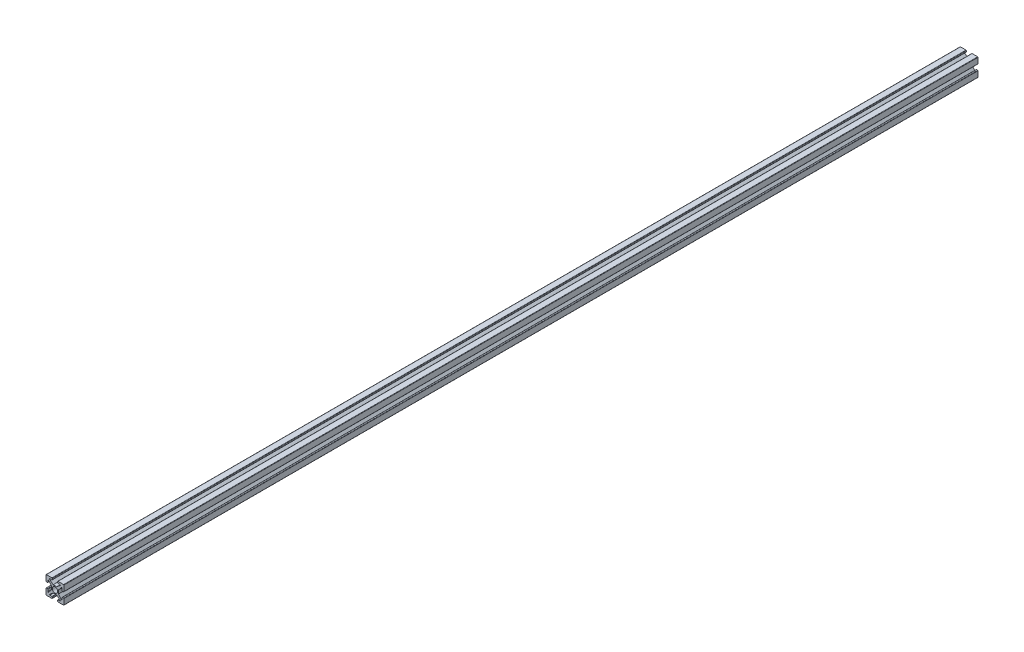
SolidWorks part; units mm, degrees
ref_plane "Front Plane" through (0, 0, 0) normal (0, 0, 1) x (1, 0, 0)
ref_plane "Top Plane" through (0, 0, 0) normal (0, 1, 0) x (1, 0, 0)
ref_plane "Right Plane" through (0, 0, 0) normal (1, 0, 0) x (0, 0, -1)
sketch "Sketch1" plane through (0, 0, 0) normal (0, 0, 1) x (1, 0, 0)
  line L0 (0, 2) -> (0, -2) construction
  line L1 (2.4868, 1) -> (2, 1) construction
  line L2 (2.4868, 1) -> (2.4868, -1) construction
  line L3 (-4.8, 5) -> (-1.7, 5)
  line L4 (2, 2) -> (0, 0) construction
  line L5 (5, 5) -> (0, 0) construction
  line L6 (-5, 5) -> (0, 0) construction
  line L7 (5, 1.7) -> (5, 4.8)
  line L8 (-2, -1) -> (-2, 1)
  line L9 (-1, 2) -> (1, 2)
  line L10 (1, 2) -> (2.9626, 3.6468)
  line L11 (2, 1) -> (3.6468, 2.9626)
  line L12 (-2, 2) -> (0, 0) construction
  line L13 (2.834, 4) -> (1.7, 4)
  line L14 (-5, 0) -> (5, 0) construction
  line L15 (-4, 1.7) -> (-4, 2.834)
  line L16 (-5, 5) -> (-1.5, 5)
  line L17 (-5, 5) -> (-5, 1.5)
  line L18 (-4.8, 1.5) -> (-4.2, 1.5)
  line L19 (-1.5, 4.8) -> (-1.5, 4.2)
  line L20 (-2.834, 4) -> (-1.7, 4)
  line L21 (-2.4868, 1) -> (-2.4868, -1) construction
  line L22 (1.5, 4.8) -> (1.5, 4.2)
  line L23 (-2, 1) -> (-3.6468, 2.9626)
  line L24 (-2.4868, 1) -> (-2, 1) construction
  line L25 (-1, 2) -> (-2.9626, 3.6468)
  line L26 (4.8, 1.5) -> (4.2, 1.5)
  line L27 (-5, 1.7) -> (-5, 4.8)
  line L28 (5, 5) -> (5, 1.5)
  line L29 (5, 5) -> (1.5, 5)
  line L30 (4, 1.7) -> (4, 2.834)
  line L31 (2, -1) -> (2, 1)
  line L32 (4.8, 5) -> (1.7, 5)
  line L33 (-2.4868, -1) -> (-2, -1) construction
  line L34 (-2, -2) -> (0, 0) construction
  line L35 (-5, -5) -> (0, 0) construction
  line L36 (5, -5) -> (0, 0) construction
  line L37 (2, -2) -> (0, 0) construction
  line L38 (2.4868, -1) -> (2, -1) construction
  line L39 (4.8, -5) -> (1.7, -5)
  line L40 (4, -1.7) -> (4, -2.834)
  line L41 (5, -5) -> (1.5, -5)
  line L42 (5, -5) -> (5, -1.5)
  line L43 (-5, -1.7) -> (-5, -4.8)
  line L44 (4.8, -1.5) -> (4.2, -1.5)
  line L45 (-1, -2) -> (-2.9626, -3.6468)
  line L46 (-2, -1) -> (-3.6468, -2.9626)
  line L47 (1.5, -4.8) -> (1.5, -4.2)
  line L48 (-2.834, -4) -> (-1.7, -4)
  line L49 (-1.5, -4.8) -> (-1.5, -4.2)
  line L50 (-4.8, -1.5) -> (-4.2, -1.5)
  line L51 (-5, -5) -> (-5, -1.5)
  line L52 (-5, -5) -> (-1.5, -5)
  line L53 (-4, -1.7) -> (-4, -2.834)
  line L54 (2.834, -4) -> (1.7, -4)
  line L55 (2, -1) -> (3.6468, -2.9626)
  line L56 (1, -2) -> (2.9626, -3.6468)
  line L57 (-1, -2) -> (1, -2)
  line L58 (5, -1.7) -> (5, -4.8)
  line L59 (-4.8, -5) -> (-1.7, -5)
  circle A0 centre (0, 0) radius 1.5
  arc A1 (-2.9626, 3.6468) -> (-2.834, 4) centre (-2.834, 3.8) cw
  arc A2 (-3.6468, 2.9626) -> (-4, 2.834) centre (-3.8, 2.834) ccw
  arc A3 (-1.7, 4) -> (-1.5, 4.2) centre (-1.7, 4.2) ccw
  arc A4 (-4, 1.7) -> (-4.2, 1.5) centre (-4.2, 1.7) cw
  arc A5 (-1.7, 5) -> (-1.5, 4.8) centre (-1.7, 4.8) cw
  arc A6 (-5, 1.7) -> (-4.8, 1.5) centre (-4.8, 1.7) ccw
  arc A7 (-5, 4.8) -> (-4.8, 5) centre (-4.8, 4.8) cw
  arc A8 (5, 4.8) -> (4.8, 5) centre (4.8, 4.8) ccw
  arc A9 (5, 1.7) -> (4.8, 1.5) centre (4.8, 1.7) cw
  arc A10 (1.7, 5) -> (1.5, 4.8) centre (1.7, 4.8) ccw
  arc A11 (4, 1.7) -> (4.2, 1.5) centre (4.2, 1.7) ccw
  arc A12 (1.7, 4) -> (1.5, 4.2) centre (1.7, 4.2) cw
  arc A13 (3.6468, 2.9626) -> (4, 2.834) centre (3.8, 2.834) cw
  arc A14 (2.9626, 3.6468) -> (2.834, 4) centre (2.834, 3.8) ccw
  arc A15 (2.9626, -3.6468) -> (2.834, -4) centre (2.834, -3.8) cw
  arc A16 (3.6468, -2.9626) -> (4, -2.834) centre (3.8, -2.834) ccw
  arc A17 (1.7, -4) -> (1.5, -4.2) centre (1.7, -4.2) ccw
  arc A18 (4, -1.7) -> (4.2, -1.5) centre (4.2, -1.7) cw
  arc A19 (1.7, -5) -> (1.5, -4.8) centre (1.7, -4.8) cw
  arc A20 (5, -1.7) -> (4.8, -1.5) centre (4.8, -1.7) ccw
  arc A21 (5, -4.8) -> (4.8, -5) centre (4.8, -4.8) cw
  arc A22 (-5, -4.8) -> (-4.8, -5) centre (-4.8, -4.8) ccw
  arc A23 (-5, -1.7) -> (-4.8, -1.5) centre (-4.8, -1.7) cw
  arc A24 (-1.7, -5) -> (-1.5, -4.8) centre (-1.7, -4.8) ccw
  arc A25 (-4, -1.7) -> (-4.2, -1.5) centre (-4.2, -1.7) ccw
  arc A26 (-1.7, -4) -> (-1.5, -4.2) centre (-1.7, -4.2) cw
  arc A27 (-3.6468, -2.9626) -> (-4, -2.834) centre (-3.8, -2.834) cw
  arc A28 (-2.9626, -3.6468) -> (-2.834, -4) centre (-2.834, -3.8) ccw
  point P0 (0, 0)
  point P4 (-3.3835, 4)
  point P6 (0, 0)
  point P7 (2, 0)
  point P10 (3.3835, -4)
  point P14 (-4, 3.3835)
  point P71 (4, 3.3835)
  point P72 (3.3835, 4)
  point P75 (-2.4868, 0)
  point P80 (2.4868, 0)
  point P129 (-2, 0)
  point P130 (4, -3.3835)
  point P131 (-4, -3.3835)
  point P132 (-3.3835, -4)
  dimension "D4" = 10
  dimension "D5" = 3
  dimension "D2" = 0.2
  dimension "D3" = 10
  dimension "D6" = 1.5
  dimension "D8" = 1
  dimension "D10" = 50
extrude "Boss-Extrude1" add sketch "Sketch1" along normal blind 511 contours A28 L45 L57 L56 A15 L54 A17 L47 A19 L39 A21 L42 A20 L44 A18 L40 A16 L55 L31 L11 A13 L30 A11 L26 A9 L7 A8 L29 A10 L22 A12 L13 A14 L10 L9 L25 A1 L20 A3 L19 A5 L3 A7 L17 A6 L18 A4 L15 A2 L23 L8
